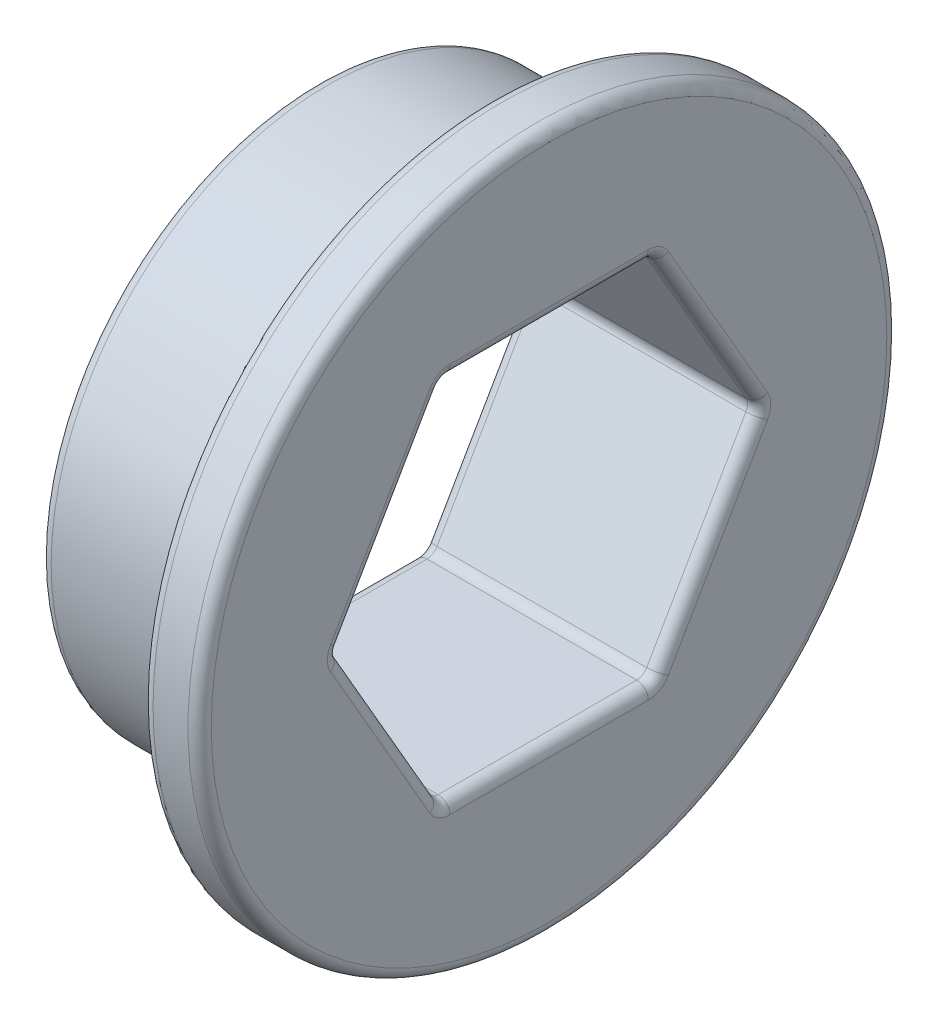
SolidWorks part; units mm, degrees
ref_plane "Front Plane" through (0, 0, 0) normal (0, 0, 1) x (1, 0, 0)
ref_plane "Top Plane" through (0, 0, 0) normal (0, 1, 0) x (1, 0, 0)
ref_plane "Right Plane" through (0, 0, 0) normal (1, 0, 0) x (0, 0, -1)
sketch "Sketch1" plane through (0, 0, 0) normal (0, 0, 1) x (1, 0, 0)
  line L0 (0, 0) -> (-8.0549, 0) construction
  line L1 (-4, 0) -> (-4, 4.75)
  line L2 (-4, 4.75) -> (-1, 4.75)
  line L3 (-1, 4.75) -> (-1, 6)
  line L4 (-1, 6) -> (0, 6)
  line L5 (0, 6) -> (0, 0)
  line L6 (0, 0) -> (-4, 0)
  dimension "D1" = 12
  dimension "D2" = 1
  dimension "D3" = 3
  dimension "D4" = 9.5
revolve "Revolve1" add sketch "Sketch1" angle 360 about L0
sketch "Sketch2" plane through (0, 0, 0) normal (1, 0, 0) x (0, 0, -1)
  line L2 (3.6373, 0) -> (1.8187, 3.15)
  line L3 (1.8187, 3.15) -> (-1.8187, 3.15)
  line L4 (-1.8187, 3.15) -> (-3.6373, 0)
  line L5 (-3.6373, 0) -> (-1.8187, -3.15)
  line L6 (-1.8187, -3.15) -> (1.8187, -3.15)
  line L7 (1.8187, -3.15) -> (3.6373, 0)
  circle A1 centre (0, 0) radius 3.15 construction
  dimension "D1" = 6.3
extrude "Cut-Extrude1" cut sketch "Sketch2" against normal up to next
fillet "Fillet1" radius 0.2 22 edges at (0, 0, -6) (-1, 0, -6) (-1, 0, -4.75) (-4, 0, -4.75) (-4, 3.15, 0) (0, 3.15, 0) (-4, -1.575, 2.728) (-4, -1.575, -2.728) (0, -1.575, -2.728) (0, -1.575, 2.728) (-4, 1.575, -2.728) (-2, 3.15, -1.8187) (0, 1.575, -2.728) (-2, 0, -3.6373) (-4, 1.575, 2.728) (-2, 0, 3.6373) (0, 1.575, 2.728) (-2, 3.15, 1.8187) (-4, -3.15, 0) (-2, -3.15, -1.8187) (0, -3.15, 0) (-2, -3.15, 1.8187)
